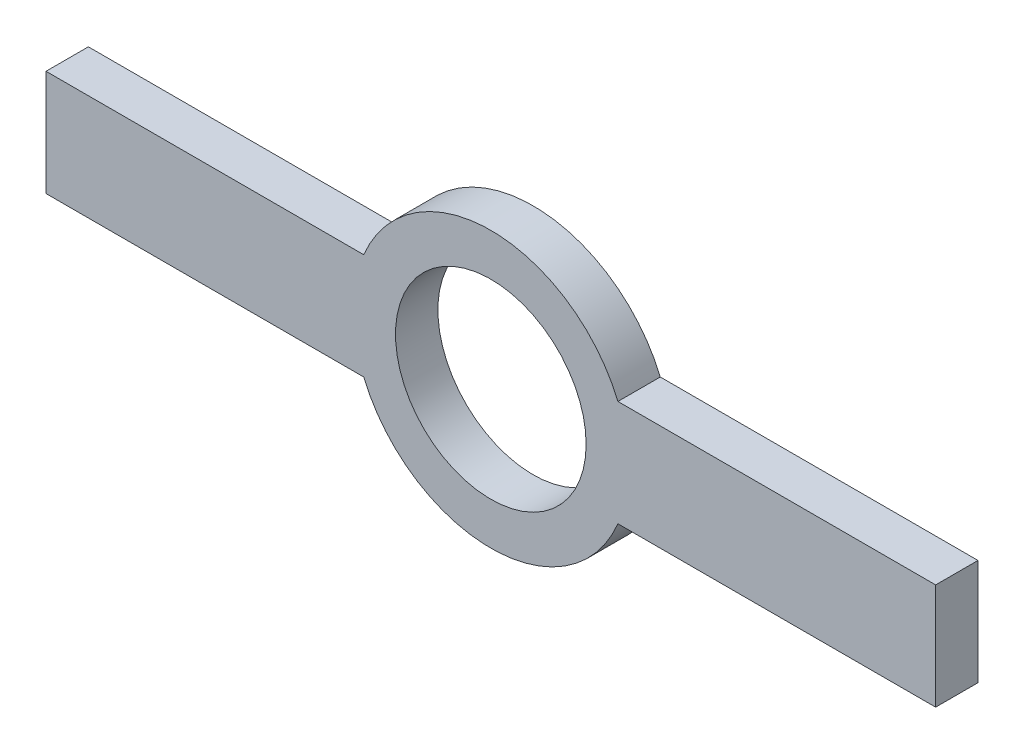
SolidWorks part; units mm, degrees
ref_plane "Piano frontale" through (0, 0, 0) normal (0, 0, 1) x (1, 0, 0)
ref_plane "Piano superiore" through (0, 0, 0) normal (0, 1, 0) x (1, 0, 0)
ref_plane "Piano destro" through (0, 0, 0) normal (1, 0, 0) x (0, 0, -1)
sketch "Schizzo2" plane through (0, 0, 0) normal (0, 0, 1) x (1, 0, 0)
  line L1 (-21, -2.5) -> (21, -2.5)
  line L2 (-21, -2.5) -> (-21, 2.5)
  line L3 (-21, 2.5) -> (21, 2.5)
  line L4 (21, -2.5) -> (21, 2.5)
  line L5 (-21, -2.5) -> (21, 2.5) construction
  line L6 (-21, 2.5) -> (21, -2.5) construction
  circle A0 centre (0, 0) radius 6.5
  point P7 (6, 2.5)
  point P8 (6, -2.5)
  point P9 (-6, 2.5)
  point P10 (-6, -2.5)
  dimension "D1" = 13
  dimension "D2" = 15
  dimension "D3" = 5
extrude "Estrusione-Estrusione1" add sketch "Schizzo2" along normal blind 2 contours A0 L3 L2 L1 | L3 A0 L1 | A0 L1 L4 L3 | L3 A0 | L1 A0
sketch "Schizzo3" plane through (0, 0, 2) normal (0, 0, 1) x (1, 0, 0)
  circle A0 centre (0, 0) radius 4.5
  dimension "D1" = 9
extrude "Taglio-Estrusione1" cut sketch "Schizzo3" against normal up to surface (2 mm away) up to face at (0, 0, 0)
